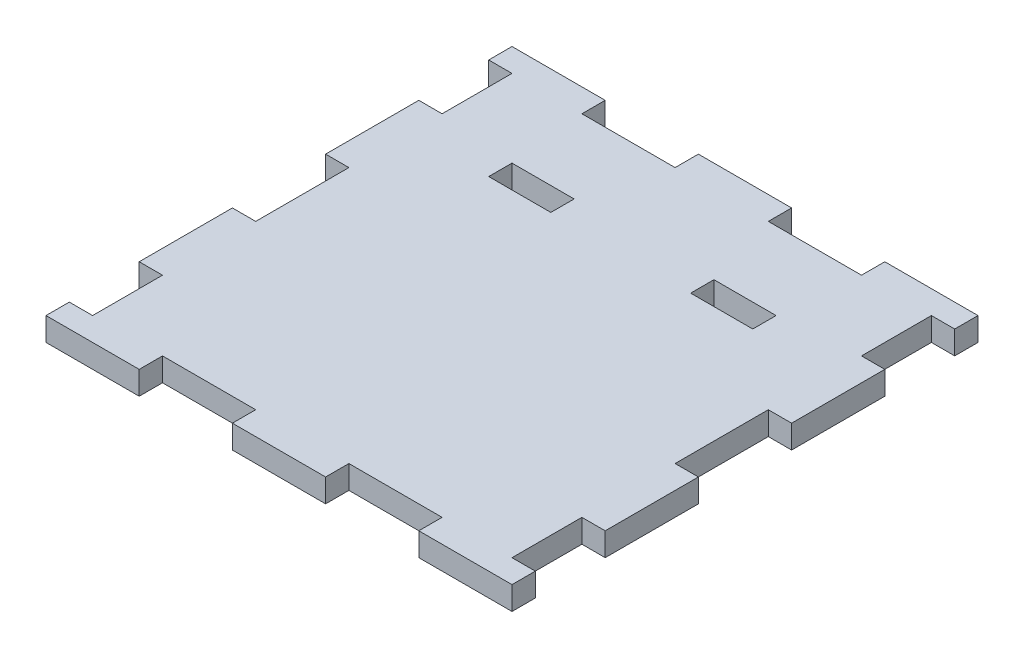
SolidWorks part; units mm, degrees
ref_plane "Front Plane" through (0, 0, 0) normal (0, 0, 1) x (1, 0, 0)
ref_plane "Top Plane" through (0, 0, 0) normal (0, 1, 0) x (1, 0, 0)
ref_plane "Right Plane" through (0, 0, 0) normal (1, 0, 0) x (0, 0, -1)
sketch "Sketch1" plane through (0, 0, 0) normal (0, 1, 0) x (1, 0, 0)
  line L1 (-33.6212, 144.0497) -> (156.8788, 144.0497)
  line L2 (-33.6212, 144.0497) -> (-33.6212, -46.4503)
  line L3 (-33.6212, -46.4503) -> (156.8788, -46.4503)
  line L4 (156.8788, 144.0497) -> (156.8788, -46.4503)
  dimension "D1" = 190.5
  dimension "D2" = 190.5
extrude "Boss-Extrude1" add sketch "Sketch1" along normal blind 9.525
sketch "Sketch2" plane through (0, 9.525, 0) normal (0, 1, 0) x (1, 0, 0)
  line L0 (-33.6212, -46.4503) -> (156.8788, -46.4503) construction
  line L1 (118.7788, -46.4503) -> (80.6788, -46.4503)
  line L2 (118.7788, -46.4503) -> (118.7788, -36.9253)
  line L3 (118.7788, -36.9253) -> (80.6788, -36.9253)
  line L4 (80.6788, -46.4503) -> (80.6788, -36.9253)
  dimension "D1" = 38.1
  dimension "D2" = 9.525
  dimension "D3" = 38.1
extrude "Cut-Extrude1" cut sketch "Sketch2" against normal blind 9.525
sketch "Sketch3" plane through (0, 9.525, 0) normal (0, 1, 0) x (1, 0, 0)
  line L0 (-33.6212, -46.4503) -> (80.6788, -46.4503) construction
  line L1 (42.5788, -46.4503) -> (4.4788, -46.4503)
  line L2 (42.5788, -46.4503) -> (42.5788, -36.9253)
  line L3 (42.5788, -36.9253) -> (4.4788, -36.9253)
  line L4 (4.4788, -46.4503) -> (4.4788, -36.9253)
  dimension "D1" = 38.1
  dimension "D2" = 9.525
  dimension "D3" = 38.1
extrude "Cut-Extrude2" cut sketch "Sketch3" against normal blind 9.525
sketch "Sketch4" plane through (0, 9.525, 0) normal (0, 1, 0) x (1, 0, 0)
  line L0 (156.8788, -46.4503) -> (156.8788, 144.0497) construction
  line L1 (156.8788, -36.9253) -> (147.3538, -36.9253)
  line L2 (156.8788, -36.9253) -> (156.8788, -8.3503)
  line L3 (156.8788, -8.3503) -> (147.3538, -8.3503)
  line L4 (147.3538, -36.9253) -> (147.3538, -8.3503)
  line L5 (118.7788, -46.4503) -> (156.8788, -46.4503) construction
  dimension "D1" = 9.525
  dimension "D2" = 28.575
  dimension "D3" = 9.525
extrude "Cut-Extrude3" cut sketch "Sketch4" against normal blind 9.525
sketch "Sketch5" plane through (0, 9.525, 0) normal (0, 1, 0) x (1, 0, 0)
  line L0 (156.8788, -8.3503) -> (156.8788, 144.0497) construction
  line L1 (156.8788, 29.7497) -> (147.3538, 29.7497)
  line L2 (156.8788, 29.7497) -> (156.8788, 67.8497)
  line L3 (156.8788, 67.8497) -> (147.3538, 67.8497)
  line L4 (147.3538, 29.7497) -> (147.3538, 67.8497)
  line L5 (156.8788, -8.3503) -> (147.3538, -8.3503) construction
  dimension "D1" = 38.1
  dimension "D2" = 9.525
  dimension "D3" = 38.1
extrude "Cut-Extrude4" cut sketch "Sketch5" against normal blind 9.525
sketch "Sketch6" plane through (0, 9.525, 0) normal (0, 1, 0) x (1, 0, 0)
  line L0 (156.8788, 67.8497) -> (156.8788, 144.0497) construction
  line L1 (156.8788, 105.9497) -> (147.3538, 105.9497)
  line L2 (156.8788, 105.9497) -> (156.8788, 134.5247)
  line L3 (156.8788, 134.5247) -> (147.3538, 134.5247)
  line L4 (147.3538, 105.9497) -> (147.3538, 134.5247)
  line L5 (156.8788, 67.8497) -> (147.3538, 67.8497) construction
  dimension "D1" = 38.1
  dimension "D2" = 9.525
  dimension "D3" = 28.575
extrude "Cut-Extrude5" cut sketch "Sketch6" against normal blind 9.525
sketch "Sketch7" plane through (0, 9.525, 0) normal (0, 1, 0) x (1, 0, 0)
  line L0 (156.8788, 144.0497) -> (-33.6212, 144.0497) construction
  line L1 (118.7788, 144.0497) -> (80.6788, 144.0497)
  line L2 (118.7788, 144.0497) -> (118.7788, 134.5247)
  line L3 (118.7788, 134.5247) -> (80.6788, 134.5247)
  line L4 (80.6788, 144.0497) -> (80.6788, 134.5247)
  dimension "D1" = 38.1
  dimension "D2" = 38.1
  dimension "D3" = 9.525
extrude "Cut-Extrude6" cut sketch "Sketch7" against normal blind 9.525
sketch "Sketch8" plane through (0, 9.525, 0) normal (0, 1, 0) x (1, 0, 0)
  line L0 (80.6788, 144.0497) -> (-33.6212, 144.0497) construction
  line L1 (42.5788, 144.0497) -> (4.4788, 144.0497)
  line L2 (42.5788, 144.0497) -> (42.5788, 134.5247)
  line L3 (42.5788, 134.5247) -> (4.4788, 134.5247)
  line L4 (4.4788, 144.0497) -> (4.4788, 134.5247)
  dimension "D1" = 38.1
  dimension "D2" = 9.525
  dimension "D3" = 38.1
extrude "Cut-Extrude7" cut sketch "Sketch8" against normal blind 9.525
sketch "Sketch9" plane through (0, 9.525, 0) normal (0, 1, 0) x (1, 0, 0)
  line L0 (-33.6212, 144.0497) -> (-33.6212, -46.4503) construction
  line L1 (-33.6212, 134.5247) -> (-24.0962, 134.5247)
  line L2 (-33.6212, 134.5247) -> (-33.6212, 105.9497)
  line L3 (-33.6212, 105.9497) -> (-24.0962, 105.9497)
  line L4 (-24.0962, 134.5247) -> (-24.0962, 105.9497)
  dimension "D1" = 9.525
  dimension "D2" = 9.525
  dimension "D3" = 28.575
extrude "Cut-Extrude8" cut sketch "Sketch9" against normal blind 38.1
sketch "Sketch10" plane through (0, 9.525, 0) normal (0, 1, 0) x (1, 0, 0)
  line L0 (-33.6212, 105.9497) -> (-33.6212, -46.4503) construction
  line L1 (-33.6212, 67.8497) -> (-24.0962, 67.8497)
  line L2 (-33.6212, 67.8497) -> (-33.6212, 29.7497)
  line L3 (-33.6212, 29.7497) -> (-24.0962, 29.7497)
  line L4 (-24.0962, 67.8497) -> (-24.0962, 29.7497)
  dimension "D1" = 38.1
  dimension "D2" = 9.525
  dimension "D3" = 38.1
extrude "Cut-Extrude9" cut sketch "Sketch10" against normal blind 9.525
sketch "Sketch11" plane through (0, 9.525, 0) normal (0, 1, 0) x (1, 0, 0)
  line L0 (-33.6212, 29.7497) -> (-33.6212, -46.4503) construction
  line L1 (-33.6212, -8.3503) -> (-24.0962, -8.3503)
  line L2 (-33.6212, -8.3503) -> (-33.6212, -36.9253)
  line L3 (-33.6212, -36.9253) -> (-24.0962, -36.9253)
  line L4 (-24.0962, -8.3503) -> (-24.0962, -36.9253)
  dimension "D1" = 28.575
  dimension "D2" = 9.525
extrude "Cut-Extrude10" cut sketch "Sketch11" against normal blind 9.525
sketch "Sketch12" plane through (0, 9.525, 0) normal (0, 1, 0) x (1, 0, 0)
  line L0 (80.6788, 134.5247) -> (118.7788, 134.5247) construction
  line L1 (7.6538, 102.7747) -> (33.0538, 102.7747)
  line L2 (7.6538, 102.7747) -> (7.6538, 93.2497)
  line L3 (7.6538, 93.2497) -> (33.0538, 93.2497)
  line L4 (33.0538, 102.7747) -> (33.0538, 93.2497)
  line L5 (-24.0962, -36.9253) -> (-24.0962, -8.3503) construction
  line L10 (90.2038, 102.7747) -> (115.6038, 102.7747)
  line L11 (90.2038, 102.7747) -> (90.2038, 93.2497)
  line L12 (90.2038, 93.2497) -> (115.6038, 93.2497)
  line L13 (115.6038, 102.7747) -> (115.6038, 93.2497)
  line L15 (147.3538, -8.3503) -> (147.3538, -36.9253) construction
  line L16 (4.4788, 134.5247) -> (42.5788, 134.5247) construction
  point P4 (20.3538, 93.2497)
  point P5 (33.0538, 98.0122)
  point P22 (0, 0)
  dimension "D1" = 9.525
  dimension "D2" = 25.4
  dimension "D3" = 31.75
  dimension "D4" = 31.75
  dimension "D5" = 9.525
  dimension "D6" = 31.75
  dimension "D7" = 25.4
  dimension "D8" = 31.75
extrude "Cut-Extrude11" cut sketch "Sketch12" against normal blind 12.7
